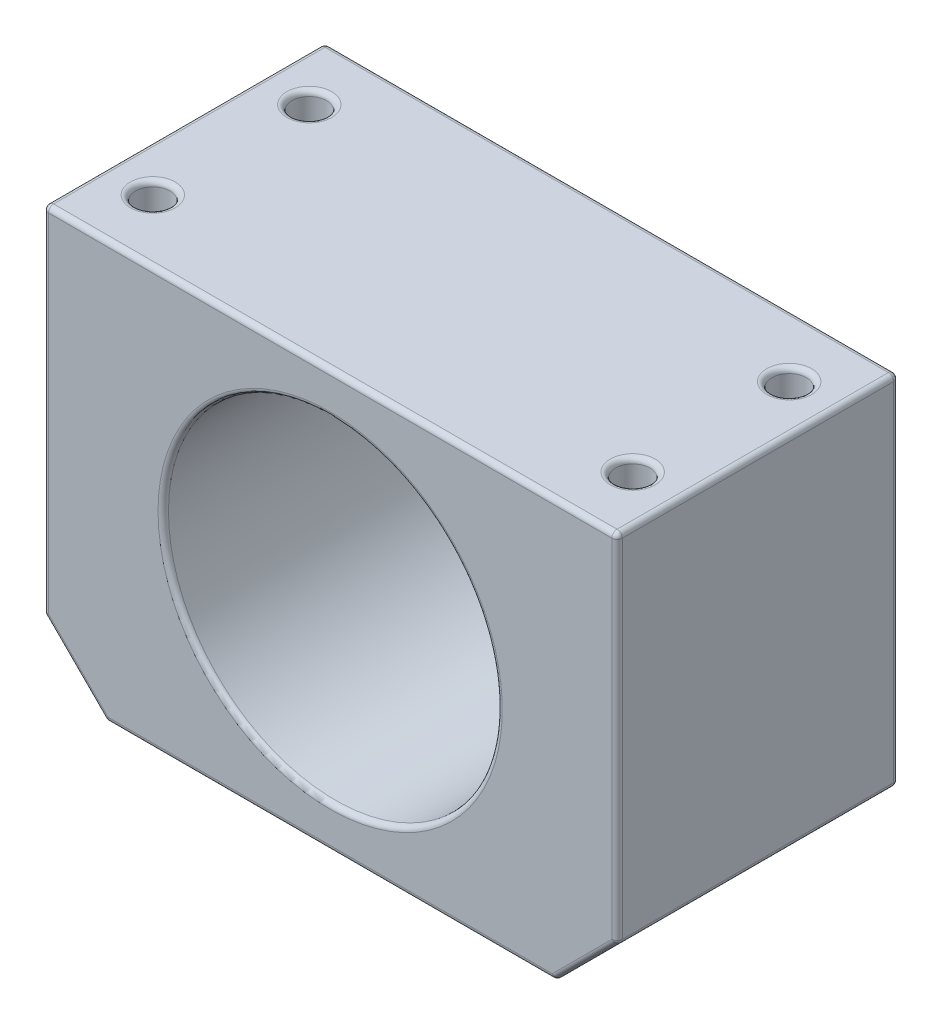
SolidWorks part; units mm, degrees
ref_plane "Front Plane" through (0, 0, 0) normal (0, 0, 1) x (1, 0, 0)
ref_plane "Top Plane" through (0, 0, 0) normal (0, 1, 0) x (1, 0, 0)
ref_plane "Right Plane" through (0, 0, 0) normal (1, 0, 0) x (0, 0, -1)
sketch "Sketch1" plane through (0, 0, 0) normal (0, 0, 1) x (1, 0, 0)
  line L0 (21.5, -20) -> (27.5, -14)
  line L1 (-27.5, 20) -> (27.5, 20)
  line L2 (-27.5, 20) -> (-27.5, -14)
  line L3 (-21.5, -20) -> (21.5, -20)
  line L4 (27.5, 20) -> (27.5, -14)
  line L5 (-27.5, 20) -> (27.5, -20) construction
  line L6 (-27.5, -20) -> (27.5, 20) construction
  line L7 (-27.5, -14) -> (-21.5, -20)
  line L8 (55, 0) -> (-55, 0) construction
  line L9 (0, -55) -> (0, 55) construction
  circle A0 centre (0, 0) radius 16
  dimension "D1" = 40
  dimension "D2" = 32
  dimension "D3" = 55
  dimension "D4" = 6
  dimension "D5" = 6
  dimension "D6" = 6
  dimension "D7" = 6
  dimension "D8" = 20
  dimension "D9" = 27.5
  dimension "D10" = 20
extrude "Boss-Extrude1" add sketch "Sketch1" along normal blind 27
hole_wizard "M4 Tapped Hole1" positions "Sketch3" profile "Sketch2" tap size "M4" standard "DIN"
sketch "Sketch3" plane through (0, 0, 0) normal (0, 0, -1) x (-1, 0, 0)
  line L0 (0, 18.5095) -> (0, -20.9479) construction
  line L1 (0, 55) -> (0, -55) construction
  line L3 (-31.1078, 0) -> (31.1078, 0) construction
  line L4 (55, 0) -> (-55, 0) construction
  line L7 (0, 0) -> (18.1865, 10.5) construction
  point P0 (18.1865, 10.5)
  point P29 (18.1865, -10.5)
  point P30 (-18.1865, -10.5)
  point P31 (-18.1865, 10.5)
  dimension "D1" = 21
  dimension "D2" = 30
cosmetic thread "Hole Thread1" parameters "D1"=8, "D2"=4
cosmetic thread "Hole Thread2" parameters "D1"=8, "D2"=4
cosmetic thread "Hole Thread3" parameters "D1"=8, "D2"=4
cosmetic thread "Hole Thread4" parameters "D1"=8, "D2"=4
sketch "Sketch2" plane through (-18.1865, 10.5, 0) normal (1, 0, 0) x (0, 1, 0)
  line L0 (0, 0) -> (0, 11.0914)
  line L1 (0, 11.0914) -> (1.65, 10.1)
  line L2 (1.65, 10.1) -> (1.65, 0)
  line L5 (1.65, 0) -> (0, 0)
  line L10 (0, 11.0914) -> (-1.65, 10.1) construction
  line L11 (0, -6.35) -> (0, 107.95) construction
  dimension "Tap Drill Dia." = 3.3
  dimension "Tap Drill Depth" = 10.1
  dimension "Drill Angle" = 118
hole_wizard "M4 Tapped Hole2" positions "Sketch5" profile "Sketch4" tap size "M4" standard "DIN"
sketch "Sketch5" plane through (0, 20, 0) normal (0, 1, 0) x (1, 0, 0)
  line L0 (0, -25.2633) -> (0, -0.5839) construction
  line L1 (0, -55) -> (0, 55) construction
  line L3 (-55, 0) -> (55, 0) construction
  line L4 (27.5, -27) -> (-27.5, -27) construction
  point P0 (23, -21)
  point P2 (23, -6)
  point P16 (-23, -6)
  point P17 (-23, -21)
  dimension "D1" = 23
  dimension "D2" = 23
  dimension "D3" = 6
  dimension "D4" = 6
sketch "Sketch4" plane through (23, 20, 21) normal (1, 0, 0) x (0, 0, 1)
  line L0 (0, 0) -> (0, 11.0914)
  line L1 (0, 11.0914) -> (1.65, 10.1)
  line L2 (1.65, 10.1) -> (1.65, 0)
  line L5 (1.65, 0) -> (0, 0)
  line L10 (0, 11.0914) -> (-1.65, 10.1) construction
  line L11 (0, -6.35) -> (0, 107.95) construction
  dimension "Tap Drill Dia." = 3.3
  dimension "Tap Drill Depth" = 10.1
  dimension "Drill Angle" = 118
cosmetic thread "Hole Thread5" parameters "D1"=8, "D2"=4
cosmetic thread "Hole Thread6" parameters "D1"=8, "D2"=4
cosmetic thread "Hole Thread7" parameters "D1"=8, "D2"=4
cosmetic thread "Hole Thread8" parameters "D1"=8, "D2"=4
fillet "Fillet1" radius 0.5 28 edges at (0, -20, 27) (-27.5, 3, 27) (16, 0, 27) (27.5, 3, 27) (16, 0, 0) (-27.5, 3, 0) (0, -20, 0) (27.5, 3, 0) (16.5365, 10.5, 0) (16.5365, -10.5, 0) (-19.8365, -10.5, 0) (-19.8365, 10.5, 0) (27.5, 20, 13.5) (0, 20, 27) (-27.5, 20, 13.5) (0, 20, 0) (-23, 20, 22.65) (-23, 20, 7.65) (23, 20, 7.65) (23, 20, 22.65) (-24.5, -17, 27) (24.5, -17, 27) (-21.5, -20, 13.5) (21.5, -20, 13.5) (-27.5, -14, 13.5) (27.5, -14, 13.5) (24.5, -17, 0) (-24.5, -17, 0)
